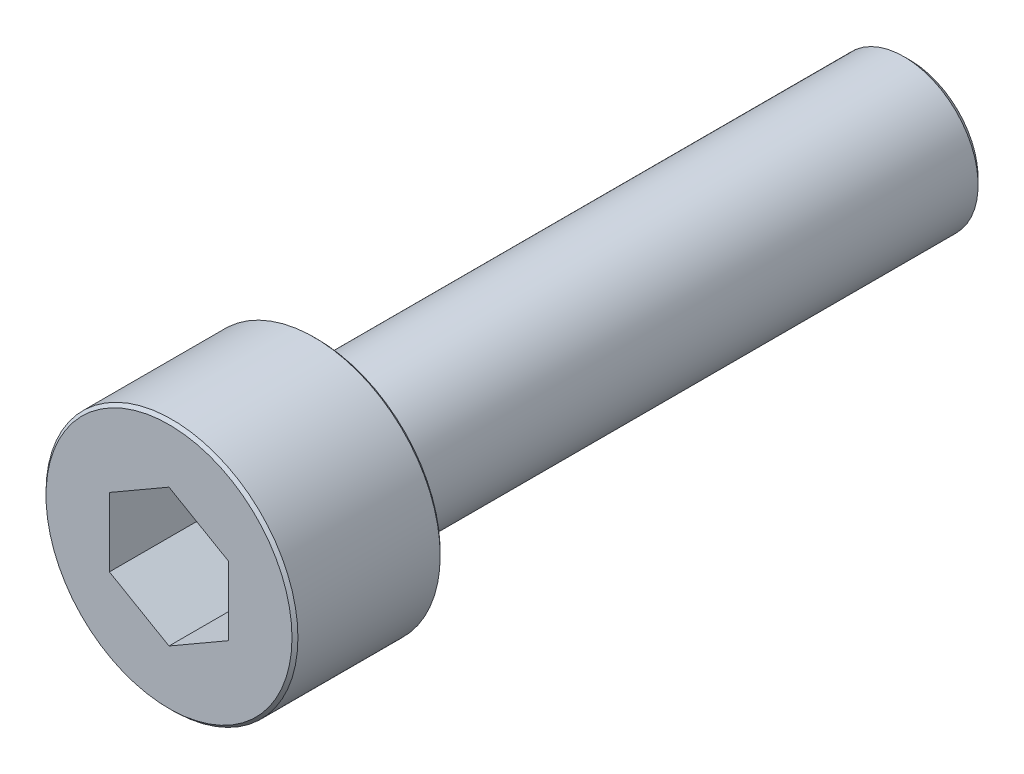
SolidWorks part; units mm, degrees
ref_plane "前视基准面" through (0, 0, 0) normal (0, 0, 1) x (1, 0, 0)
ref_plane "上视基准面" through (0, 0, 0) normal (0, 1, 0) x (1, 0, 0)
ref_plane "右视基准面" through (0, 0, 0) normal (1, 0, 0) x (0, 0, -1)
other "Configuration Table"
sketch "草图1" plane through (0, 0, 0) normal (0, 1, 0) x (1, 0, 0)
  line L0 (4.25, -20) -> (0, -20)
  line L1 (0, -20) -> (0, -25)
  line L2 (0, -25) -> (4.25, -25)
  line L3 (4.25, -25) -> (4.25, -20)
  line L4 (0, -20) -> (0, -25) construction
revolve "旋转1" add sketch "草图1" angle 360 about L4
sketch "草图2" plane through (0, 0, 20) normal (0, 0, -1) x (-1, 0, 0)
  circle A0 centre (0, 0) radius 2.5
extrude "凸台-拉伸1" add sketch "草图2" along normal blind 20
sketch "草图3" plane through (0, 0, 25) normal (0, 0, 1) x (1, 0, 0)
  line L0 (-2.01, -1.1605) -> (0, -2.3209)
  line L1 (0, -2.3209) -> (2.01, -1.1605)
  line L2 (2.01, -1.1605) -> (2.01, 1.1605)
  line L3 (2.01, 1.1605) -> (0, 2.3209)
  line L4 (0, 2.3209) -> (-2.01, 1.1605)
  line L5 (-2.01, 1.1605) -> (-2.01, -1.1605)
extrude "切除-拉伸1" cut sketch "草图3" against normal blind 3.75
chamfer "倒角1" distance 0.1 angle 45 2 edges at (4.25, 0, 20) (4.25, 0, 25)
chamfer "倒角2" distance 0.2 angle 45 1 edges at (-2.5, 0, 0)
